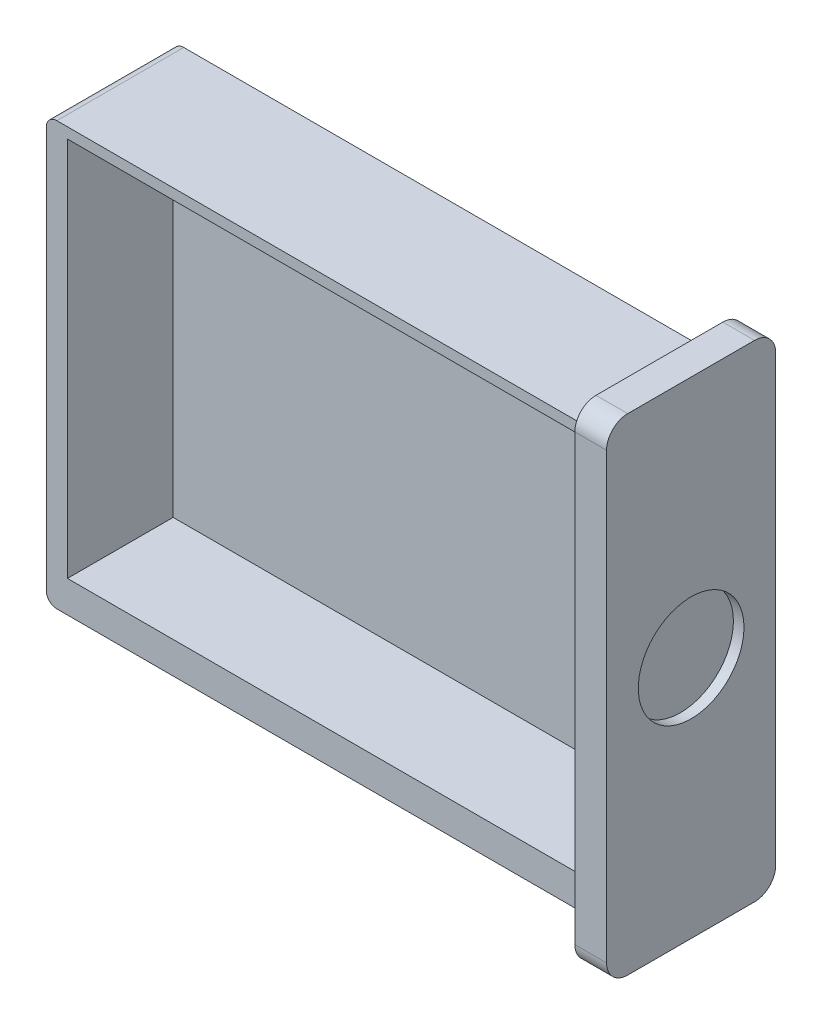
SolidWorks part; units mm, degrees
ref_plane "Front Plane" through (0, 0, 0) normal (0, 0, 1) x (1, 0, 0)
ref_plane "Top Plane" through (0, 0, 0) normal (0, 1, 0) x (1, 0, 0)
ref_plane "Right Plane" through (0, 0, 0) normal (1, 0, 0) x (0, 0, -1)
sketch "Sketch1" plane through (0, 0, 0) normal (0, 0, 1) x (1, 0, 0)
  line L1 (-26, 20) -> (26, 20)
  line L2 (-26, 20) -> (-26, -20)
  line L3 (-26, -20) -> (26, -20)
  line L4 (26, 20) -> (26, -20)
  point P4 (0, 20)
  point P6 (26, 0)
  dimension "D1" = 52
  dimension "D2" = 40
extrude "Boss-Extrude1" add sketch "Sketch1" along normal mid plane 12
fillet "Fillet1" radius 1 4 edges at (-26, -20, 0) (26, -20, 0) (-26, 20, 0) (26, 20, 0)
sketch "Sketch2" plane through (0, 0, 6) normal (0, 0, 1) x (1, 0, 0)
  line L1 (-24, 19) -> (24, 19)
  line L2 (-24, 19) -> (-24, -17)
  line L3 (-24, -17) -> (24, -17)
  line L4 (24, 19) -> (24, -17)
  point P4 (24, 1)
  point P5 (0, 19)
  dimension "D1" = 48
  dimension "D2" = 36
  dimension "D3" = 1
extrude "Cut-Extrude1" cut sketch "Sketch2" against normal blind 10
ref_plane "Plane4" through (26, 0, 0) normal (1, 0, 0) x (0, 0, -1)
sketch "Sketch3" plane through (26, 0, 0) normal (1, 0, 0) x (0, 0, -1)
  line L1 (-8, 23) -> (8, 23)
  line L2 (-8, 23) -> (-8, -23)
  line L3 (-8, -23) -> (8, -23)
  line L4 (8, 23) -> (8, -23)
  point P4 (0, 23)
  point P6 (8, 0)
  dimension "D1" = 46
  dimension "D2" = 16
extrude "Boss-Extrude2" add sketch "Sketch3" along normal blind 3
fillet "Fillet2" radius 2 4 edges at (27.5, -23, -8) (27.5, -23, 8) (27.5, 23, -8) (27.5, 23, 8)
sketch "Sketch4" plane through (29, 0, 0) normal (1, 0, 0) x (0, 0, -1)
  circle A0 centre (0, 0) radius 5
  dimension "D1" = 10
extrude "Cut-Extrude2" cut sketch "Sketch4" against normal blind 1
sketch "Sketch5" plane through (-26, 0, 0) normal (-1, 0, 0) x (0, 0, 1)
  line L0 (8.8, 0) -> (-8.8, 0) construction
  line L1 (-1.5, 11) -> (1.5, 11)
  line L2 (-1.5, 11) -> (-1.5, 5)
  line L3 (-1.5, 5) -> (1.5, 5)
  line L4 (1.5, 11) -> (1.5, 5)
  line L5 (1.5, -11) -> (1.5, -5)
  line L6 (-1.5, -5) -> (1.5, -5)
  line L7 (-1.5, -11) -> (-1.5, -5)
  line L8 (-1.5, -11) -> (1.5, -11)
  point P4 (0, 11)
  point P6 (1.5, 8)
  dimension "D1" = 3
  dimension "D2" = 6
  dimension "D3" = 8
extrude "Boss-Extrude3" add sketch "Sketch5" along normal blind 1
